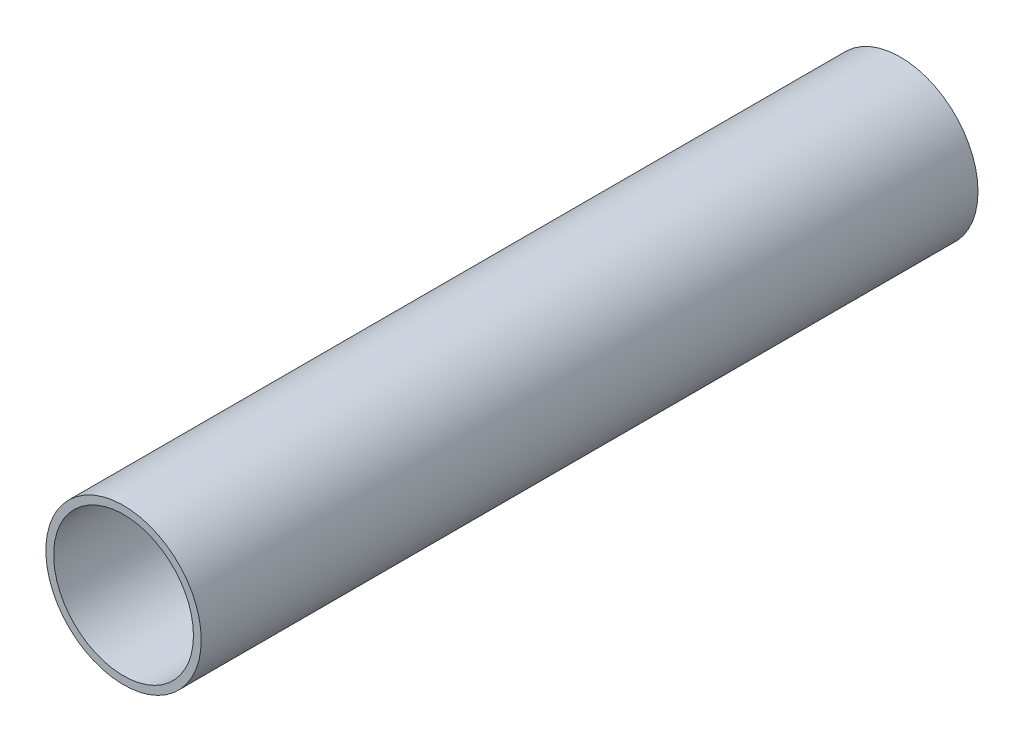
SolidWorks part; units mm, degrees
other "Defeature"
material "6061 Alloy"
ref_plane "Front Plane" through (0, 0, 0) normal (0, 0, 1) x (1, 0, 0)
ref_plane "Top Plane" through (0, 0, 0) normal (0, 1, 0) x (1, 0, 0)
ref_plane "Right Plane" through (0, 0, 0) normal (1, 0, 0) x (0, 0, -1)
sketch "Sketch1" plane through (0, 0, 0) normal (0, 0, 1) x (1, 0, 0)
  circle A0 centre (0, 0) radius 8
  circle A1 centre (0, 0) radius 7.2
  dimension "D1" = 16
  dimension "D2" = 0.8
extrude "Boss-Extrude1" add sketch "Sketch1" along normal mid plane 80 contours A0 A1
